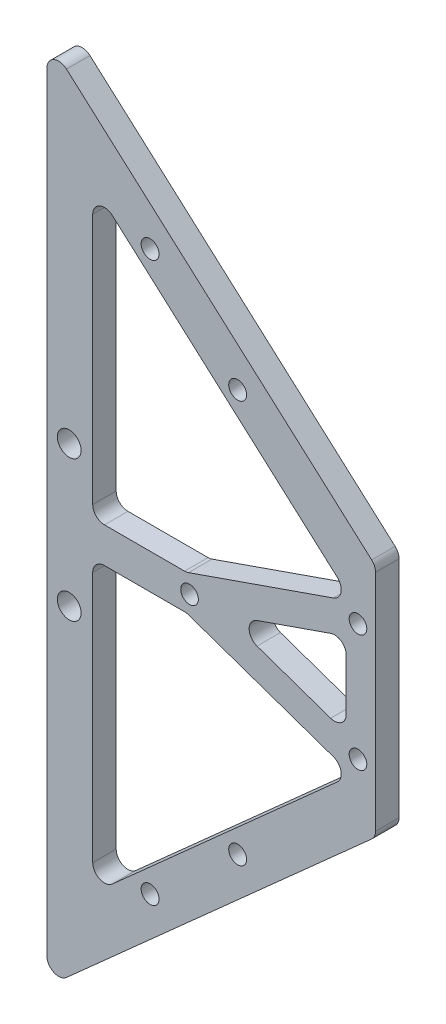
SolidWorks part; units mm, degrees
material "Thornel Mat VMA"
ref_plane "前视基准面" through (0, 0, 0) normal (0, 0, 1) x (1, 0, 0)
ref_plane "上视基准面" through (0, 0, 0) normal (0, 1, 0) x (1, 0, 0)
ref_plane "右视基准面" through (0, 0, 0) normal (1, 0, 0) x (0, 0, -1)
other "Configuration Table"
sketch "草图1" plane through (0, 0, 0) normal (0, 0, 1) x (1, 0, 0)
  line L1 (-28, -20) -> (28, -20)
  line L2 (-28, -20) -> (-28, 20)
  line L3 (-28, 20) -> (28, 20)
  line L4 (28, -20) -> (28, 20)
  line L5 (-28, -20) -> (28, 20) construction
  line L6 (-28, 20) -> (28, -20) construction
  point P0 (0, 0)
  dimension "D1" = 40
  dimension "D2" = 56
extrude "凸台-拉伸1" add sketch "草图1" along normal blind 4
sketch "草图2" plane through (0, 0, 0) normal (0, 0, -1) x (-1, 0, 0)
  circle A0 centre (3.7, 0) radius 1.5 construction
  circle A1 centre (-25, 10) radius 1.5 construction
  circle A2 centre (-25, -10) radius 1.5 construction
  circle A3 centre (3.7, 0) radius 1.5
  circle A4 centre (-25, 10) radius 1.5
  circle A5 centre (-25, -10) radius 1.5
  circle A6 centre (24.2, -12) radius 2.025 construction
  circle A7 centre (24.2, 12) radius 2.025 construction
  circle A8 centre (7.7, -9) radius 1.025 construction
  circle A9 centre (15.7, -9) radius 1.025 construction
  circle A10 centre (24.2, -12) radius 2.025
  circle A11 centre (24.2, 12) radius 2.025
  circle A12 centre (7.7, -9) radius 1.025
  circle A13 centre (15.7, -9) radius 1.025
extrude "切除-拉伸1" cut sketch "草图2" against normal blind 34
sketch "草图3" plane through (0, 0, 4) normal (0, 0, 1) x (1, 0, 0)
  line L0 (28, 20) -> (-28, 70)
  line L1 (-28, 70) -> (-28, 20)
  line L2 (-28, 20) -> (28, 20)
  line L3 (0, 0) -> (36.711, 0) construction
  dimension "D1" = 70
extrude "凸台-拉伸2" add sketch "草图3" against normal up to surface (4 mm away) up to face at (23.5, 10, 0)
mirror "镜向1" about plane through (0, 0, 0) normal (0, 1, 0) of "凸台-拉伸2"
sketch "草图4" plane through (0, 0, 0) normal (0, 0, -1) x (-1, 0, 0)
  circle A0 centre (10.4207, -47.6012) radius 1.25 construction
  circle A1 centre (-4.4981, -34.2809) radius 1.25 construction
  circle A2 centre (10.4207, -47.6012) radius 1.25 construction
  circle A3 centre (-4.4981, -34.2809) radius 1.25 construction
  circle A4 centre (10.4207, -47.6012) radius 1.525
  circle A5 centre (-4.4981, -34.2809) radius 1.525
  dimension "D1" = 3.05
extrude "切除-拉伸2" cut sketch "草图4" against normal blind 10
mirror "镜向2" about plane through (0, 0, 0) normal (0, 1, 0) of "切除-拉伸2"
fillet "圆角1" radius 2 4 edges at (-28, 70, 2) (28, 20, 2) (28, -20, 2) (-28, -70, 2)
sketch "草图5" plane through (0, 0, 0) normal (0, 0, -1) x (-1, 0, 0)
  line L0 (-25, 10) -> (3.7, 0) construction
  line L1 (3.7, 0) -> (-25, -10) construction
  line L2 (-25, -10) -> (-25, 10) construction
  line L3 (-23, 7.1852) -> (-2.3785, 0)
  line L4 (-2.3785, 0) -> (-23, -7.1852)
  line L5 (-23, -7.1852) -> (-23, 7.1852)
  line L6 (20.2, 52.311) -> (-24.0147, 12.8336)
  line L7 (-24.0147, 12.8336) -> (4.2077, 3)
  line L8 (4.2077, 3) -> (20.2, 3)
  line L9 (20.2, 3) -> (20.2, 52.311)
  line L10 (10.4207, 47.6012) -> (-4.4981, 34.2809) construction
  line L11 (15.7, 0) -> (28, 0) construction
  line L12 (28, 65.5331) -> (28, -65.5331) construction
  line L13 (4.2077, -3) -> (20.2, -3)
  line L14 (-24.0147, -12.8336) -> (4.2077, -3)
  line L15 (20.2, -52.311) -> (-24.0147, -12.8336)
  line L16 (20.2, -3) -> (20.2, -52.311)
  circle A0 centre (24.2, 12) radius 2.025 construction
  circle A1 centre (15.7, -9) radius 1.025 construction
  dimension "D2" = 4
  dimension "D3" = 3
  dimension "D4" = 3
  dimension "D5" = 12
  dimension "D1" = 2
extrude "切除-拉伸3" cut sketch "草图5" against normal blind 22
fillet "圆角2" radius 2 11 edges at (2.3785, 0, 2) (23, -7.1852, 2) (23, 7.1852, 2) (-4.2077, 3, 2) (24.0147, 12.8336, 2) (-20.2, 52.311, 2) (-20.2, 3, 2) (-20.2, -3, 2) (-20.2, -52.311, 2) (24.0147, -12.8336, 2) (-4.2077, -3, 2)
